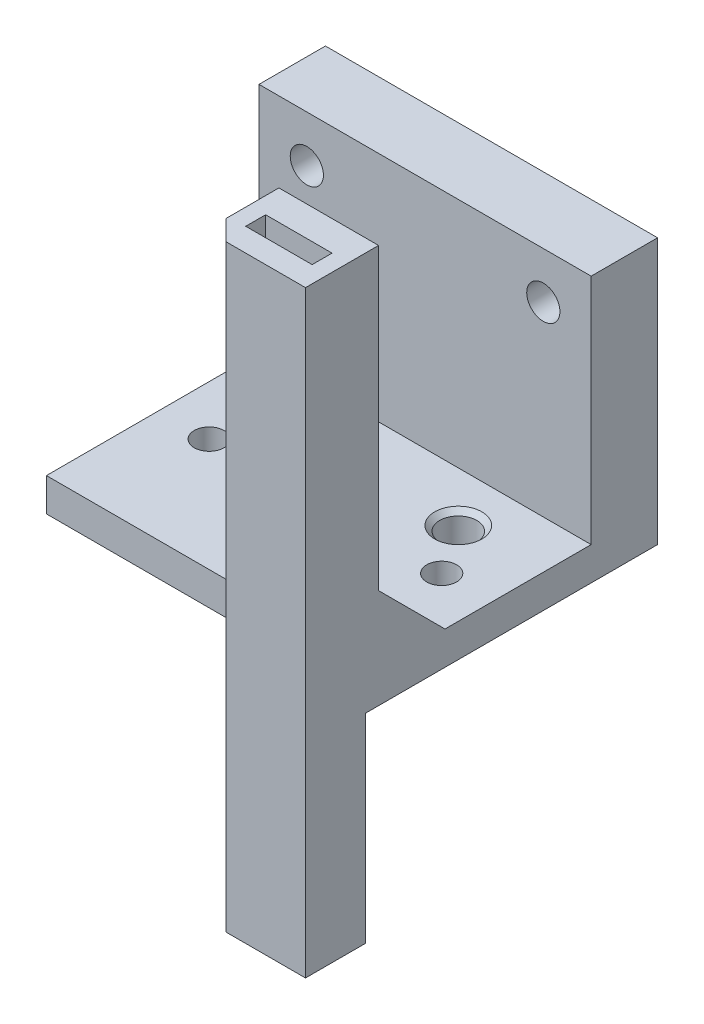
SolidWorks part; units mm, degrees
material "PET"
ref_plane "Front Plane" through (0, 0, 0) normal (0, 0, 1) x (1, 0, 0)
ref_plane "Top Plane" through (0, 0, 0) normal (0, 1, 0) x (1, 0, 0)
ref_plane "Right Plane" through (0, 0, 0) normal (1, 0, 0) x (0, 0, -1)
sketch "Sketch1" plane through (0, 0, 0) normal (0, 1, 0) x (1, 0, 0)
  line L0 (-30, 15) -> (30, 15) construction
  line L2 (-25, 0) -> (-25, 40)
  line L3 (-25, 40) -> (25, 40)
  line L4 (25, 0) -> (25, 40)
  line L5 (0, 0) -> (25, 40) construction
  line L6 (-25, 40) -> (0, 0) construction
  line L7 (-25, 22.5) -> (25, 22.5) construction
  line L8 (-25, 0) -> (-25, -2)
  line L11 (-25, -2) -> (25, -2)
  line L12 (25, -2) -> (25, 0)
  line L13 (-25, 0) -> (25, 0) construction
  line L14 (0, 0) -> (0, 40) construction
  circle A0 centre (-12.5, 22.5) radius 2.8
  circle A1 centre (12.5, 22.5) radius 2.8
  circle A3 centre (-17.5, 15) radius 2.25
  circle A4 centre (17.5, 15) radius 2.25
  circle A6 centre (0, 6) radius 2.8
  point P0 (0, 0)
  point P22 (0, 40)
  point P23 (0, 40)
  dimension "D6" = 5.6
  dimension "D7" = 5.6
  dimension "D8" = 4.5
  dimension "D9" = 4.5
  dimension "D5" = 5.6
  dimension "D2" = 50
  dimension "D4" = 17.5
  dimension "D12" = 25
  dimension "D17" = 40
  dimension "D18" = 25
  dimension "D3" = 2
  dimension "D13" = 6
  dimension "D14" = 12.5
  dimension "D15" = 12.5
  dimension "D10" = 17.5
  dimension "D11" = 17.5
extrude "Boss-Extrude1" add sketch "Sketch1" along normal blind 5
sketch "Sketch3" plane through (0, 5, 0) normal (0, 1, 0) x (1, 0, 0)
  line L2 (-25, 40) -> (-25, 30)
  line L3 (-25, 30) -> (25, 30)
  line L5 (25, 40) -> (-25, 40)
  line L6 (25, 40) -> (25, 30)
  dimension "D2" = 10
extrude "Boss-Extrude3" add sketch "Sketch3" along normal blind 35
sketch "Sketch4" plane through (0, 0, -40) normal (0, 0, -1) x (-1, 0, 0)
  line L0 (-25, 0) -> (25, 0) construction
  line L2 (-17.8, 33) -> (17.8, 33) construction
  circle A0 centre (-17.8, 33) radius 2.5
  circle A1 centre (17.8, 33) radius 2.5
  dimension "D3" = 5
  dimension "D4" = 5
  dimension "D1" = 17.8
  dimension "D2" = 35.6
  dimension "D5" = 33
extrude "Cut-Extrude1" cut sketch "Sketch4" against normal through all
chamfer "Chamfer1" distance 0.75 angle 45 3 edges at (-12.5, 5, -19.7) (12.5, 5, -19.7) (0, 5, -3.2)
sketch "Sketch5" plane through (0, 0, 0) normal (0, -1, 0) x (1, 0, 0)
  line L0 (13, 13) -> (10, 10)
  line L1 (25, 2) -> (10, 2)
  line L2 (25, 2) -> (25, 13)
  line L3 (25, 13) -> (13, 13)
  line L6 (10, 2) -> (10, 10)
  line L7 (22.5, 9.5) -> (12.5, 9.5)
  line L8 (22.5, 9.5) -> (22.5, 6.5)
  line L9 (22.5, 6.5) -> (12.5, 6.5)
  line L10 (12.5, 9.5) -> (12.5, 6.5)
  dimension "D1" = 11
  dimension "D2" = 12
  dimension "D3" = 10
  dimension "D4" = 2.5
  dimension "D5" = 3
  dimension "D6" = 4.5
  dimension "D7" = 15
  dimension "D8" = 135
extrude "Boss-Extrude4" add sketch "Sketch5" along normal blind 30 and the other way blind 60
chamfer "Chamfer2" distance 10 angle 45 1 edges at (17.5, 5, 2)
chamfer "Chamfer3" distance 5 angle 45 2 edges at (10, 5, -3) (10, 2.5, 2)
sketch "Sketch7" plane through (25, 0, 0) normal (1, 0, 0) x (0, 0, -1)
  line L0 (-2, -30) -> (-13, -30) construction
  line L1 (-2, 0) -> (-4, 0)
  line L2 (-2, 0) -> (-2, -30)
  line L3 (-2, -30) -> (-4, -30)
  line L4 (-4, 0) -> (-4, -30)
  dimension "D1" = 2
extrude "Cut-Extrude2" cut sketch "Sketch7" against normal through all
equation "\"D18@Sketch1\"=\"D2@Sketch1\"/2"
equation "\"D1@Sketch4\"=\"D2@Sketch4\"/2"
